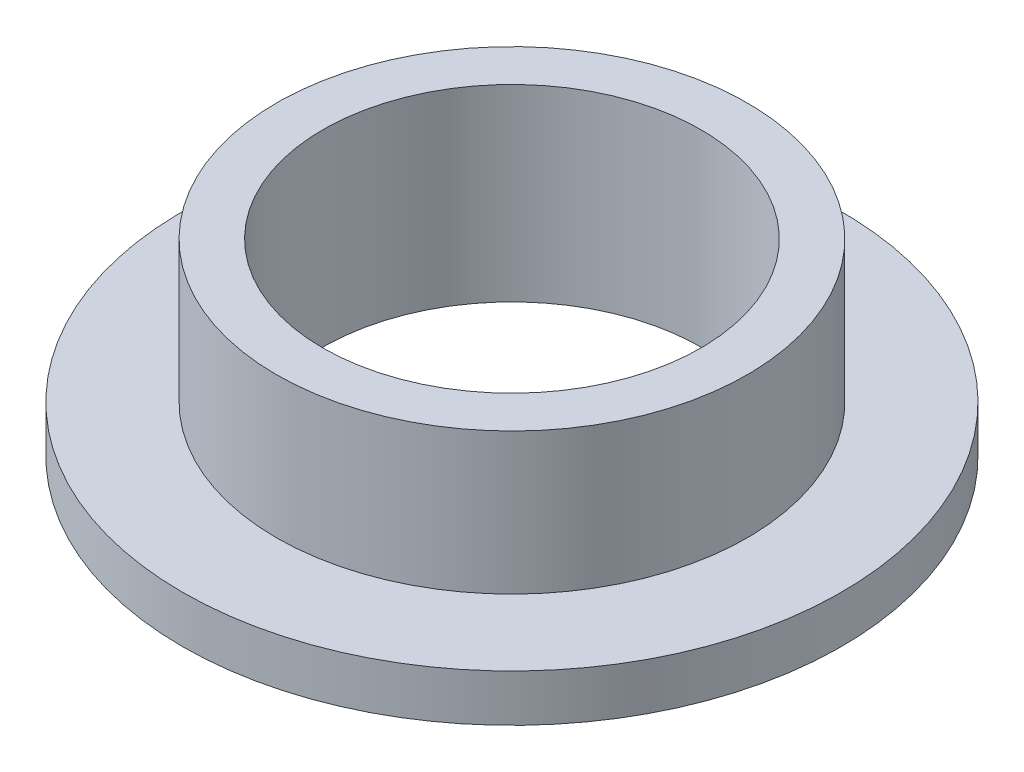
SolidWorks part; units mm, degrees
ref_plane "Front" through (0, 0, 0) normal (0, 0, 1) x (1, 0, 0)
ref_plane "Top" through (0, 0, 0) normal (0, 1, 0) x (1, 0, 0)
ref_plane "Right" through (0, 0, 0) normal (1, 0, 0) x (0, 0, -1)
sketch "Sketch1" plane through (0, 0, 0) normal (0, 1, 0) x (1, 0, 0)
  circle A0 centre (0, 0) radius 6.3754
  circle A1 centre (0, 0) radius 7.9375
  circle A2 centre (0, 0) radius 11.1125
  dimension "ID" = 12.7508
  dimension "OD" = 15.875
  dimension "FlangeOD" = 22.225
sketch "Sketch2" plane through (0, 0, 0) normal (0, 1, 0) x (1, 0, 0)
  circle A0 centre (0, 0) radius 6.3754 construction
  circle A1 centre (0, 0) radius 7.9375 construction
  circle A2 centre (0, 0) radius 6.3754
  circle A3 centre (0, 0) radius 7.9375
extrude "Boss-Extrude1" add sketch "Sketch2" along normal blind 6.35
sketch "Sketch3" plane through (0, 0, 0) normal (0, 1, 0) x (1, 0, 0)
  circle A0 centre (0, 0) radius 11.1125 construction
  circle A1 centre (0, 0) radius 7.9375 construction
  circle A2 centre (0, 0) radius 11.1125
  circle A3 centre (0, 0) radius 7.9375
extrude "Boss-Extrude2" add sketch "Sketch3" along normal blind 1.5875
